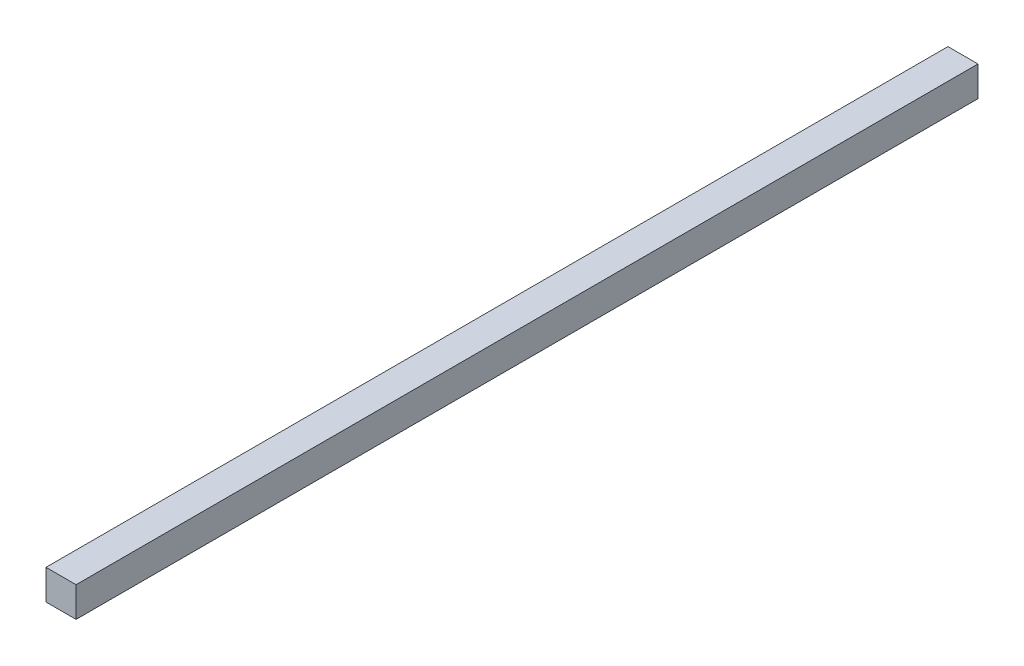
SolidWorks part; units mm, degrees
ref_plane "Plan de face" through (0, 0, 0) normal (0, 0, 1) x (1, 0, 0)
ref_plane "Plan de dessus" through (0, 0, 0) normal (0, 1, 0) x (1, 0, 0)
ref_plane "Plan de droite" through (0, 0, 0) normal (1, 0, 0) x (0, 0, -1)
sketch "Esquisse1" plane through (0, 0, 0) normal (0, 0, 1) x (1, 0, 0)
  line L1 (-15, -15) -> (15, -15)
  line L2 (-15, -15) -> (-15, 15)
  line L3 (-15, 15) -> (15, 15)
  line L4 (15, -15) -> (15, 15)
  line L5 (-15, -15) -> (15, 15) construction
  line L6 (-15, 15) -> (15, -15) construction
  point P0 (15, 0)
  dimension "D1" = 15
  dimension "D2" = 30
  dimension "D3" = 15
extrude "Boss.-Extru.1" add sketch "Esquisse1" along normal blind 900
